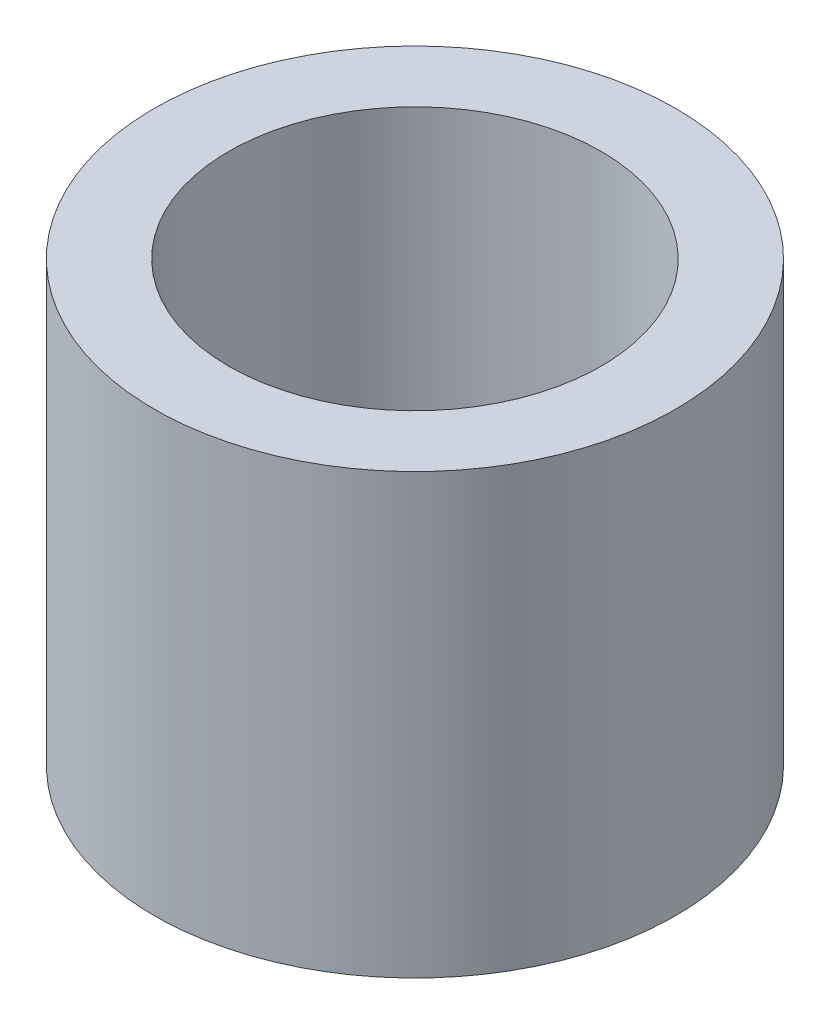
SolidWorks part; units mm, degrees
ref_plane "Front Plane" through (0, 0, 0) normal (0, 0, 1) x (1, 0, 0)
ref_plane "Top Plane" through (0, 0, 0) normal (0, 1, 0) x (1, 0, 0)
ref_plane "Right Plane" through (0, 0, 0) normal (1, 0, 0) x (0, 0, -1)
sketch "Sketch1" plane through (0, 0, 0) normal (0, 1, 0) x (1, 0, 0)
  circle A0 centre (0, 0) radius 3.5
  circle A1 centre (0, 0) radius 2.5
  dimension "D1" = 5
  dimension "D2" = 7
extrude "Boss-Extrude1" add sketch "Sketch1" along normal blind 5.8903
